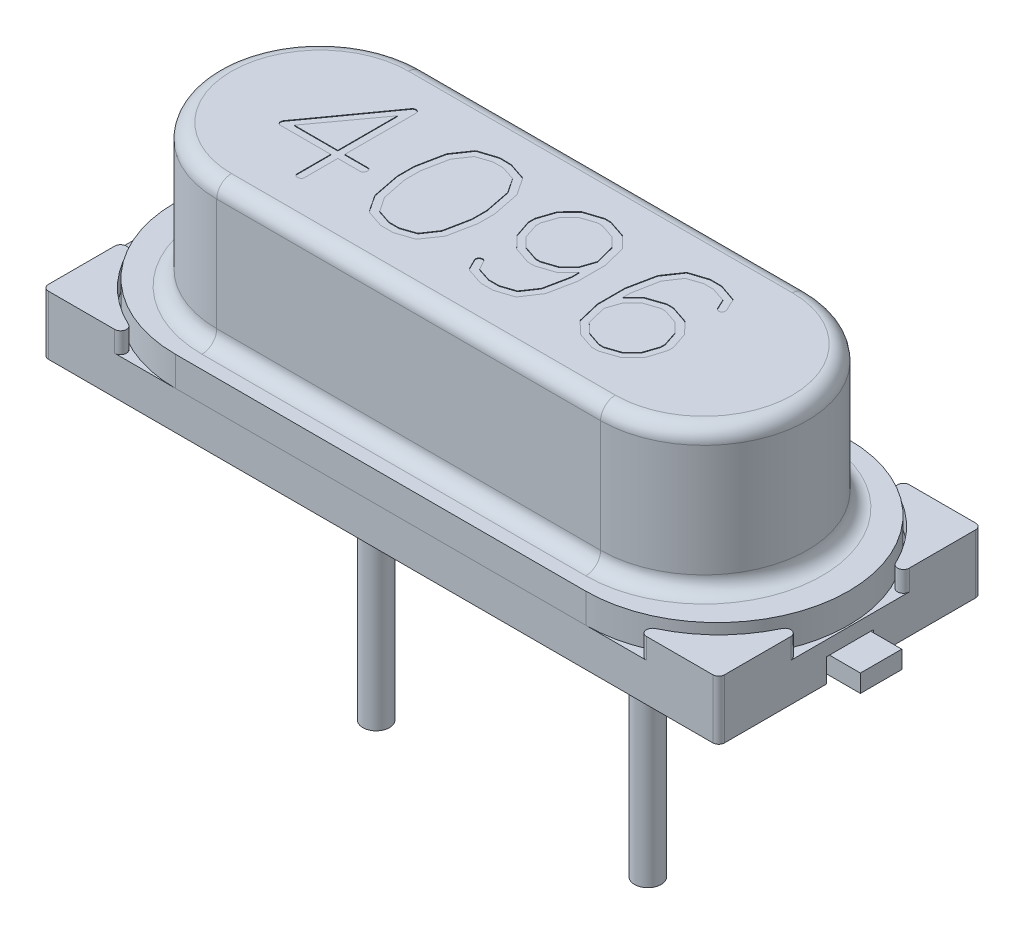
SolidWorks part; units mm, degrees
ref_plane "Front Plane" through (0, 0, 0) normal (0, 0, 1) x (1, 0, 0)
ref_plane "Top Plane" through (0, 0, 0) normal (0, 1, 0) x (1, 0, 0)
ref_plane "Right Plane" through (0, 0, 0) normal (1, 0, 0) x (0, 0, -1)
sketch "Sketch1" plane through (0, 0, 0) normal (0, 1, 0) x (1, 0, 0)
  line L1 (-5.725, 2.225) -> (5.725, 2.225)
  line L2 (-5.725, 2.225) -> (-5.725, -2.225)
  line L3 (-5.725, -2.225) -> (5.725, -2.225)
  line L4 (5.725, 2.225) -> (5.725, -2.225)
  line L5 (-5.725, 2.225) -> (5.725, -2.225) construction
  line L6 (-5.725, -2.225) -> (5.725, 2.225) construction
  point P0 (0, 0)
  dimension "D1" = 11.45
  dimension "D2" = 4.45
extrude "Boss-Extrude1" add sketch "Sketch1" against normal blind 1
sketch "Sketch2" plane through (0, 0, 0) normal (0, 1, 0) x (1, 0, 0)
  line L0 (-3.5, 0) -> (3.5, 0) construction
  line L1 (-3.5, 2.25) -> (3.5, 2.25)
  line L2 (-3.5, -2.25) -> (3.5, -2.25)
  line L3 (5.75, 0) -> (5.75, 5.2042) construction
  line L4 (-5.75, 0) -> (-5.75, 5.2042) construction
  arc A0 (-3.5, 2.25) -> (-3.5, -2.25) centre (-3.5, 0) ccw
  arc A1 (3.5, -2.25) -> (3.5, 2.25) centre (3.5, 0) ccw
  point P2 (0, 0)
  dimension "D1" = 4.5
  dimension "D2" = 11.5
extrude "Cut-Extrude2" cut sketch "Sketch2" against normal blind 0.35
fillet "Fillet1" radius 0.1 12 edges at (-5.725, -0.5, 2.225) (-5.725, -0.5, -2.225) (5.725, -0.5, -2.225) (5.725, -0.5, 2.225) (3.8345, -0.175, 2.225) (5.725, -0.175, -0.3345) (5.725, -0.175, 0.3345) (3.8345, -0.175, -2.225) (-3.8345, -0.175, -2.225) (-5.725, -0.175, 0.3345) (-5.725, -0.175, -0.3345) (-3.8345, -0.175, 2.225)
sketch "Sketch3" plane through (0, -0.35, 0) normal (0, 1, 0) x (1, 0, 0)
  line L0 (-3.475, 0) -> (3.475, 0) construction
  line L1 (-3.475, 2.225) -> (3.475, 2.225)
  line L2 (-3.475, -2.225) -> (3.475, -2.225)
  line L3 (5.7, 0) -> (5.7, 3.6957) construction
  line L4 (-5.7, 0) -> (-5.7, 3.6957) construction
  arc A0 (-3.475, 2.225) -> (-3.475, -2.225) centre (-3.475, 0) ccw
  arc A1 (3.475, -2.225) -> (3.475, 2.225) centre (3.475, 0) ccw
  point P2 (0, 0)
  dimension "D1" = 11.4
  dimension "D2" = 4.45
extrude "Boss-Extrude2" add sketch "Sketch3" along normal blind 0.5 separate body
sketch "Sketch4" plane through (0, 0.15, 0) normal (0, 1, 0) x (1, 0, 0)
  line L2 (-3.25, 0) -> (3.25, 0) construction
  line L3 (-3.25, 1.75) -> (3.25, 1.75)
  line L4 (-3.25, -1.75) -> (3.25, -1.75)
  line L5 (5, 0) -> (-5, 0) construction
  arc A2 (-3.25, 1.75) -> (-3.25, -1.75) centre (-3.25, 0) ccw
  arc A3 (3.25, -1.75) -> (3.25, 1.75) centre (3.25, 0) ccw
  point P2 (0, 0)
  dimension "D1" = 3.5
  dimension "D2" = 10
extrude "Boss-Extrude3" add sketch "Sketch4" along normal blind 2.4
fillet "Fillet2" radius 0.25 8 edges at (-5, 0.15, 0) (0, 0.15, -1.75) (5, 0.15, 0) (-5, 2.55, 0) (0, 2.55, -1.75) (5, 2.55, 0) (0, 0.15, 1.75) (0, 2.55, 1.75)
sketch "Sketch5" plane through (0, 2.55, 0) normal (0, 1, 0) x (1, 0, 0)
  line L0 (-4.4108, -0.95) -> (4.4108, -0.95) construction
  line L1 (3.25, 1.75) -> (-3.25, 1.75) construction
  arc A0 (-3.25, 1.5) -> (-3.25, -1.5) centre (-3.25, 0) ccw construction
  arc A1 (3.25, -1.5) -> (3.25, 1.5) centre (3.25, 0) ccw construction
  text T0 "4096\r\n" font "SWSimp" height 2
  dimension "D1" = 2.7
extrude "Cut-Extrude3" cut sketch "Sketch5" against normal blind 0.01
sketch "Sketch6" plane through (0, -1, 0) normal (0, -1, 0) x (1, 0, 0)
  line L0 (0, 3.2884) -> (0, -3.5226) construction
  line L1 (0, 0) -> (-6.0373, 0) construction
  line L2 (-2.2, 0.4) -> (-7.8383, 0.4)
  line L3 (-2.2, 0.4) -> (-2.2, -0.4)
  line L4 (-2.2, -0.4) -> (-7.8383, -0.4)
  line L5 (-7.8383, 0.4) -> (-7.8383, -0.4)
  line L6 (2.2, -0.4) -> (7.8383, -0.4)
  line L7 (7.8383, 0.4) -> (7.8383, -0.4)
  line L8 (2.2, 0.4) -> (7.8383, 0.4)
  line L9 (2.2, 0.4) -> (2.2, -0.4)
  dimension "D1" = 4.4
  dimension "D2" = 0.8
extrude "Cut-Extrude4" cut sketch "Sketch6" against normal blind 0.4
sketch "Sketch7" plane through (0, -0.6, 0) normal (0, -1, 0) x (1, 0, 0)
  line L4 (5.675, 0.35) -> (6.25, 0.35)
  line L5 (6.25, 0.35) -> (6.25, -0.35)
  line L6 (6.25, -0.35) -> (5.675, -0.35)
  line L7 (0, 3.4984) -> (0, -3.58) construction
  line L8 (5.675, 0.35) -> (2.25, 0.35)
  line L9 (2.25, 0.35) -> (2.25, -0.35)
  line L10 (2.25, -0.35) -> (5.675, -0.35)
  line L11 (5.675, -0.35) -> (5.675, 0.35)
  line L12 (5.675, 0.35) -> (2.25, 0.35)
  line L13 (2.25, 0.35) -> (2.25, -0.35)
  line L14 (2.25, -0.35) -> (5.675, -0.35)
  line L16 (-5.675, 0.35) -> (-6.25, 0.35)
  line L17 (-6.25, 0.35) -> (-6.25, -0.35)
  line L18 (-6.25, -0.35) -> (-5.675, -0.35)
  line L19 (-2.25, -0.35) -> (-5.675, -0.35)
  line L20 (-2.25, 0.35) -> (-2.25, -0.35)
  line L21 (-5.675, 0.35) -> (-2.25, 0.35)
  dimension "D2" = 12.5
  dimension "D1" = 0.05
extrude "Boss-Extrude4" add sketch "Sketch7" along normal blind 0.3 separate body
sketch "Sketch8" plane through (0, -0.35, 0) normal (0, -1, 0) x (1, 0, 0)
  line L0 (0, 3.4464) -> (0, -3.9228) construction
  circle A0 centre (2.3, 0) radius 0.825
  circle A1 centre (-2.3, 0) radius 0.825
  point P5 (0, 0)
  dimension "D2" = 1.65
  dimension "D1" = 4.6
extrude "Cut-Extrude5" cut sketch "Sketch8" against normal blind 0.01
sketch "Sketch9" plane through (0, -0.34, 0) normal (0, -1, 0) x (1, 0, 0)
  line L0 (0, 2.6355) -> (0, -3.1631) construction
  circle A0 centre (2.3, 0) radius 0.225
  circle A1 centre (-2.3, 0) radius 0.225
  dimension "D1" = 0.45
extrude "Boss-Extrude5" add sketch "Sketch9" along normal blind 5.4 separate body
